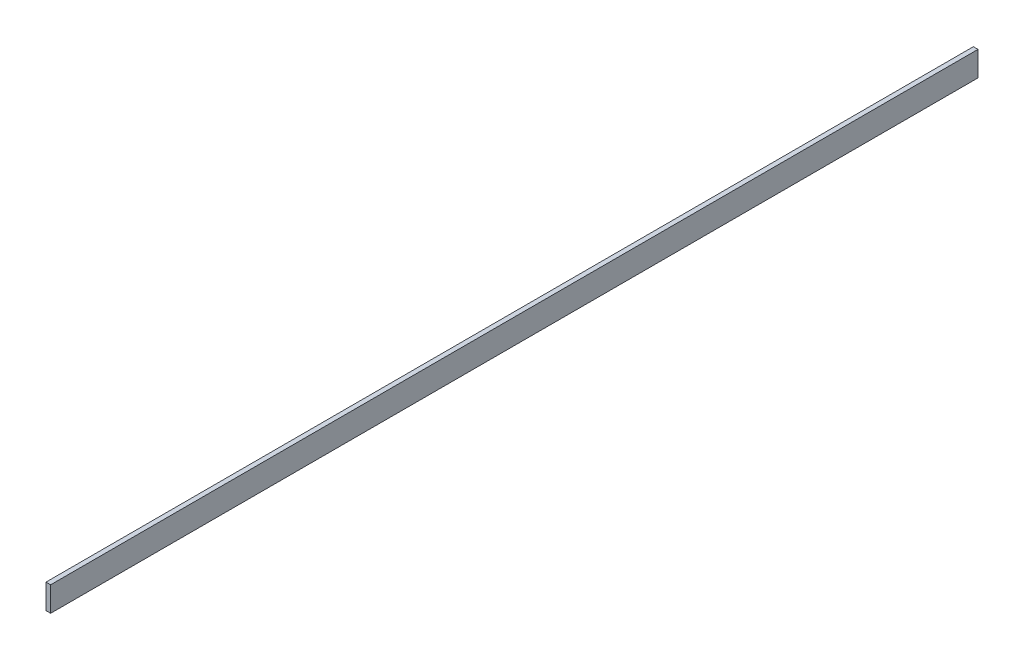
SolidWorks part; units mm, degrees
ref_plane "Спереди" through (0, 0, 0) normal (0, 0, 1) x (1, 0, 0)
ref_plane "Сверху" through (0, 0, 0) normal (0, 1, 0) x (1, 0, 0)
ref_plane "Справа" through (0, 0, 0) normal (1, 0, 0) x (0, 0, -1)
sketch "Эскиз1" plane through (0, 0, 0) normal (0, 0, 1) x (1, 0, 0)
  line L1 (0, 0) -> (3, 0)
  line L2 (0, 0) -> (0, 16)
  line L3 (0, 16) -> (3, 16)
  line L4 (3, 0) -> (3, 16)
  dimension "D1" = 3
  dimension "D2" = 16
extrude "Бобышка-Вытянуть1" add sketch "Эскиз1" along normal blind 600
